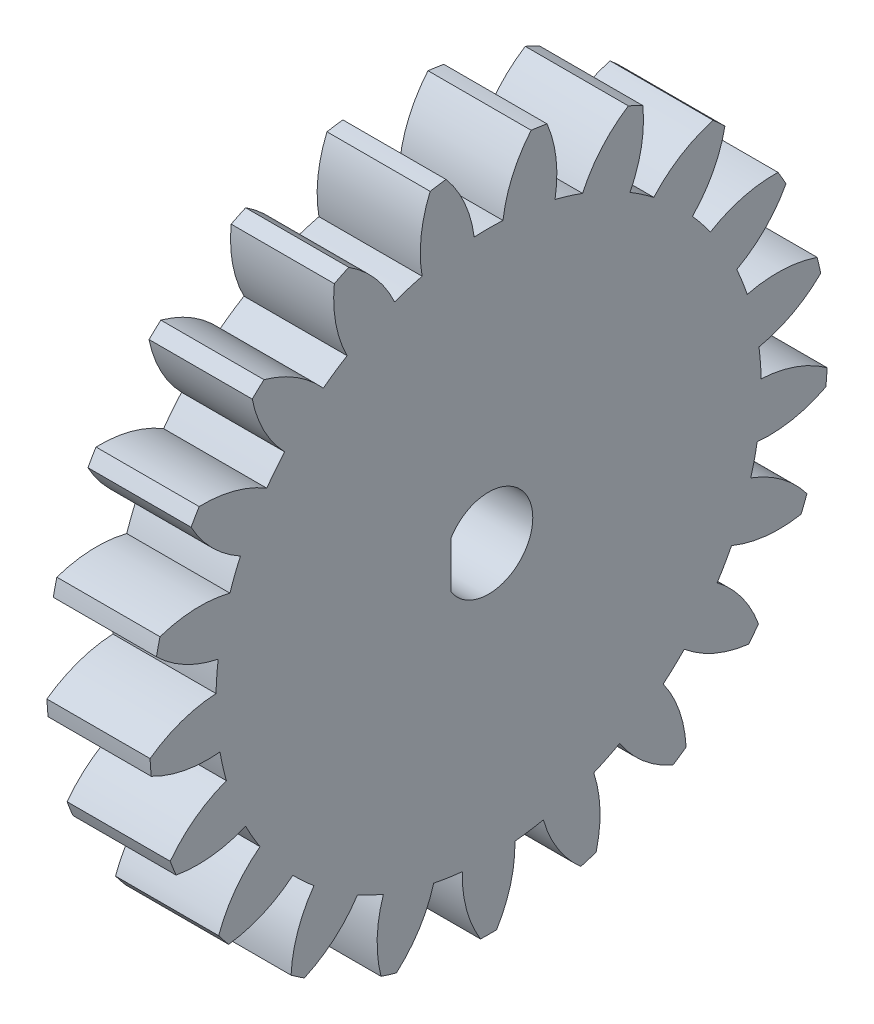
SolidWorks part; units mm, degrees
ref_plane "Plane1" through (0, 0, 0) normal (0, 0, 1) x (1, 0, 0)
ref_plane "Plane2" through (0, 0, 0) normal (0, 1, 0) x (1, 0, 0)
ref_plane "Plane3" through (0, 0, 0) normal (1, 0, 0) x (0, 0, -1)
other "Configuration Table"
sketch "HoldingSke" plane through (0, 0, 0) normal (0, 1, 0) x (1, 0, 0)
  line L0 (0, 0) -> (0.4668, -0.1792)
  line L1 (-15, 0) -> (100, 0) construction
  line L2 (0, 0) -> (-2.1039, 2.3779)
  line L3 (0, 0) -> (-11.863, 4.5341)
  line L4 (0, 0) -> (8.0624, 3.0949)
  line L5 (0, 0) -> (-11.2434, -4.1935)
  line L6 (0, 0) -> (-5.8027, -3.9151)
  line L7 (-2.1039, 2.3779) -> (0.4791, 14.0966)
  line L8 (-76.2, 54.61) -> (-75.2, 54.61)
  line L9 (-71.009, 38.7566) -> (-53.1078, 45.2721)
  line L10 (-76.2, 71.12) -> (104.1128, 71.12)
  line L11 (0, 0) -> (-7, 0)
  line L12 (-76.2, 101.6) -> (-76.133, 101.6)
  line L13 (24.9733, 27.94) -> (52.9518, 28.4284)
  line L14 (24.9733, 27.94) -> (24.9743, 27.94)
  line L15 (24.9733, 27.94) -> (100.4006, 29.5858)
  line L16 (-63.627, -2) -> (-12.827, -2)
  circle A0 centre (0, 0) radius 3
  circle A1 centre (0, 0) radius 5
  circle A2 centre (0, 0) radius 5
  circle A3 centre (0, 0) radius 3
  dimension "MHD" = 10
  dimension "Hub_dia" = 10
  dimension "Bore" = 6
  dimension "MBD" = 6
  dimension "Num_teeth" = 21
  dimension "Pitch" = 0.5
  dimension "Overall_len" = 12
  dimension "Show_teeth" = 21
  dimension "Thickness" = 7
  dimension "OAL" = 12.0001
  dimension "T_dim" = 1
  dimension "Ap" = 20
  dimension "H" = 19.05
  dimension "Pitch_radius" = 180.3128
  dimension "Width" = 7
  dimension "Backlash" = 0.067
  dimension "Addendum_fac" = 1
  dimension "Dedendum_fac" = 1.25
  dimension "Clearance_fac" = 0.25
  dimension "Dedendum_add" = 0.001
  dimension "Module" = 2
sketch "BasProSke" plane through (0, 0, 0) normal (0, 1, 0) x (1, 0, 0)
  line L0 (-10, 0) -> (60, 0) construction
  line L1 (0, 0) -> (0, 23)
  line L2 (0, 0) -> (7, 0)
  line L3 (7, 0) -> (7, 23)
  line L4 (7, 23) -> (0, 23)
  dimension "Thickness" = 7
  dimension "Diameter" = 46
revolve "Base-Revolve" add sketch "BasProSke" angle 360 about L0
sketch "TooCutSke" plane through (0, 0, 0) normal (1, 0, 0) x (0, 0, -1)
  line L1 (0, 0) -> (0, 107) construction
  line L2 (0, 0) -> (-1.6865, 20.9322) construction
  line L3 (0, 0) -> (-6.2448, 41.4315) construction
  line L4 (-1.6865, 20.9322) -> (-3.1224, 20.7157) construction
  arc A0 (0.9768, 18.4732) -> (-0.9768, 18.4732) centre (0, 0) ccw
  arc A1 (2.908, 22.841) -> (-2.908, 22.841) centre (0, 0) ccw
  circle A2 centre (0, 0) radius 21 construction
  circle A3 centre (0, 0) radius 19.7335 construction
  arc A4 (-0.9768, 18.4732) -> (-2.908, 22.841) centre (-9.308, 17.4004) ccw
  arc A5 (2.908, 22.841) -> (0.9768, 18.4732) centre (9.308, 17.4004) ccw
  dimension "Root_dia" = 36.998
  dimension "Overcut_dia" = 46.0508
  dimension "Pitch_dia" = 42
  dimension "Base_dia" = 39.4671
  dimension "Flank_rad" = 8.4
  dimension "Half_ang" = 8.571
  dimension "Half_CT" = 1.4521
extrude "ToothCut" cut sketch "TooCutSke" along normal through all
fillet "Breaks" [suppressed] radius 0.04
fillet "RootFillets" [suppressed] radius 0.501
pattern_circular "TeethCuts" count 21 every 17.143 about axis through (-10, 0, 0) along (1, 0, 0) of "ToothCut", "RootFillets", "Breaks"
sketch "HubNeaOneSke" plane through (0, 0, 0) normal (-1, 0, 0) x (0, 0, 1)
  circle A0 centre (0, 0) radius 5
  dimension "Diameter" = 10
extrude "HubNearOne" add sketch "HubNeaOneSke" along normal blind 5.0001
sketch "HubNeaBotSke" plane through (0, 0, 0) normal (-1, 0, 0) x (0, 0, 1)
  circle A0 centre (0, 0) radius 5
  dimension "Diameter" = 10
extrude "HubNearBoth" [suppressed] add sketch "HubNeaBotSke" along normal blind 2.5
ref_plane "FarPln" through (7, 0, 0) normal (1, 0, 0) x (0, 0, -1)
sketch "HubFarSke" plane through (7, 0, 0) normal (1, 0, 0) x (0, 0, -1)
  circle A0 centre (0, 0) radius 5
  dimension "Diameter" = 10
extrude "HubFar" [suppressed] add sketch "HubFarSke" along normal blind 2.5
sketch "BorSke" plane through (0, 0, 0) normal (1, 0, 0) x (0, 0, -1)
  circle A0 centre (0, 0) radius 3
  dimension "Diameter" = 6
extrude "Bore" cut sketch "BorSke" along normal mid plane 24.0001
sketch "KeySke" plane through (0, 0, 0) normal (1, 0, 0) x (0, 0, -1)
  line L0 (-1, 0) -> (-1, 4)
  line L1 (-1, 4) -> (1, 4)
  line L2 (1, 4) -> (1, 0)
  line L3 (0, 0) -> (0, 34) construction
  line L4 (-1, 0) -> (1, 0)
  dimension "Offset" = 4
  dimension "Width" = 2
extrude "Keyway" [suppressed] cut sketch "KeySke" along normal mid plane 24.0001
pattern_circular "Keyway2" [suppressed] count 2 every 90 about axis through (-10, 0, 0) along (1, 0, 0)
sketch "草图1" plane through (-5.0001, 0, 0) normal (-1, 0, 0) x (0, 0, 1)
  line L0 (2.55, 1.5803) -> (2.55, -1.5803)
  arc A0 (2.55, -1.5803) -> (2.55, 1.5803) centre (0, 0) ccw
  dimension "D2" = 6
  dimension "D1" = 2.55
extrude "凸台-拉伸1" add sketch "草图1" against normal through all
sketch "草图3" plane through (0, 0, 0) normal (0, 0, 1) x (1, 0, 0)
  line L1 (-7.99, 0) -> (4.3508, 0) construction
  circle A0 centre (-2.5001, 0) radius 1.65
  dimension "D1" = 3.3
sketch "草图4" plane through (-5.0001, 0, 0) normal (-1, 0, 0) x (0, 0, 1)
  line L0 (0, -1.65) -> (0, 1.65) construction
  line L1 (-4, 3) -> (-4, -3)
  line L2 (4, 3) -> (4, -3)
  arc A0 (-4, 3) -> (-4, -3) centre (0, 0) ccw
  arc A1 (4, -3) -> (4, 3) centre (0, 0) ccw
  dimension "D2" = 4
  dimension "D3" = 10
  dimension "D1" = 4
extrude "切除-拉伸2" cut sketch "草图4" against normal up to surface (5.0001 mm away) up to face at (0, 0, -5)
extrude "切除-拉伸3" cut sketch "草图3" against normal through all both and the other way through all
equation "' \"Module@HoldingSke\" = 6.35"
equation "' \"Num_teeth@HoldingSke\" = 12"
equation "' \"Ap@HoldingSke\" =  20"
equation "' \"Ap@HoldingSke\" = 20"
equation "' \"Width@HoldingSke\" = 0.5 * 25.4"
equation "' \"Hub_dia@HoldingSke\"= 1 * 25.4"
equation "' \"Hub_dia@HoldingSke\" = 1 * 25.4"
equation "' \"Overall_len@HoldingSke\" = 1.0 * 25.4"
equation "' \"Bore@HoldingSke\" = 0.75 * 25.4"
equation "' \"T_dim@HoldingSke\" = 0.1 * 25.4"
equation "' \"Width@KeySke\" = 0.25 * 25.4"
equation "' \"Show_teeth@HoldingSke\" = 13"
equation "' \"Backlash@HoldingSke\" = 0.009 * 25.4"
equation "' \"Addendum_fac@HoldingSke\" = 1.0"
equation "' \"Dedendum_fac@HoldingSke\" = 1.25"
equation "' \"Dedendum_add@HoldingSke\" = 0.00005 * 25.4"
equation "' \"Clearance_fac@HoldingSke\" = 0.25"
equation "\"Pitch@HoldingSke\" = 1 / \"Module@HoldingSke\""
equation "\"Overcut_dia@TooCutSke\" = (\"Num_teeth@HoldingSke\" + 2 * \"Addendum_fac@HoldingSke\") / \"Pitch@HoldingSke\" + 0.002 * 25.4"
equation "\"Pitch_dia@TooCutSke\" = \"Num_teeth@HoldingSke\" / \"Pitch@HoldingSke\""
equation "\"Base_dia@TooCutSke\" = \"Num_teeth@HoldingSke\" / \"Pitch@HoldingSke\" * cos((\"Ap@HoldingSke\"  * 3.14159265 / 180))"
equation "\"Root_dia@TooCutSke\" = (\"Num_teeth@HoldingSke\" + 2) / \"Pitch@HoldingSke\" - 2 * (\"Addendum_fac@HoldingSke\" + \"Dedendum_fac@HoldingSke\") / \"Pitch@HoldingSke\" - \"Dedendum_add@HoldingSke\" * 2"
equation "\"Half_ang@TooCutSke\" = 180 / \"Num_teeth@HoldingSke\""
equation "\"Half_CT@TooCutSke\" = \"Num_teeth@HoldingSke\" / \"Pitch@HoldingSke\" * sin((3.14159265 / 2 / \"Num_teeth@HoldingSke\")) / 2 - 7 * \"Backlash@HoldingSke\" / 4"
equation "\"Flank_rad@TooCutSke\" = \"Num_teeth@HoldingSke\" / \"Pitch@HoldingSke\" / 5"
equation "\"Radius@RootFillets\" = \"Clearance_fac@HoldingSke\" / \"Pitch@HoldingSke\" + \"Dedendum_add@HoldingSke\""
equation "\"Break_rad@Breaks\" = 0.02 / \"Pitch@HoldingSke\""
equation "\"Thickness@HoldingSke\" = \"Width@HoldingSke\""
equation "\"OAL@HoldingSke\" = \"Thickness@HoldingSke\""
equation "\"MHD@HoldingSke\" = (\"Num_teeth@HoldingSke\" + 2) / \"Pitch@HoldingSke\" - 2 * (\"Addendum_fac@HoldingSke\" + \"Dedendum_fac@HoldingSke\")  / \"Pitch@HoldingSke\" - \"Dedendum_add@HoldingSke\" * 2"
equation "\"MBD@HoldingSke\" = (\"Num_teeth@HoldingSke\" + 2) / \"Pitch@HoldingSke\" - 2 * (\"Addendum_fac@HoldingSke\" + \"Dedendum_fac@HoldingSke\")  / \"Pitch@HoldingSke\" - \"Dedendum_add@HoldingSke\" * 2 - 0.002 * 25.4"
equation "\"MHD@HoldingSke\" = ((sgn( \"MHD@HoldingSke\" - \"Hub_dia@HoldingSke\" )-1)*( \"MHD@HoldingSke\" - \"Hub_dia@HoldingSke\" ))/-2+ \"Hub_dia@HoldingSke\""
equation "\"MBD@HoldingSke\" = ((sgn( \"MBD@HoldingSke\" - \"Bore@HoldingSke\" )-1)*( \"MBD@HoldingSke\" - \"Bore@HoldingSke\" ))/-2+ \"Bore@HoldingSke\""
equation "\"OAL@HoldingSke\" = ((sgn( \"OAL@HoldingSke\" - \"Overall_len@HoldingSke\" )+1)*( \"OAL@HoldingSke\" - \"Overall_len@HoldingSke\" ))/2 + \"Overall_len@HoldingSke\" + 0.000002 * 25.4"
equation "\"Num_teeth@TeethCuts\" = int( \"Show_teeth@HoldingSke\" ) + 1"
equation "\"Num_teeth@TeethCuts\" = ((sgn( \"Num_teeth@TeethCuts\" - \"Num_teeth@HoldingSke\" )-1)*( \"Num_teeth@TeethCuts\" - \"Num_teeth@HoldingSke\" ))/-2+ \"Num_teeth@HoldingSke\""
equation "\"Num_teeth@TeethCuts\" = ((sgn( \"Num_teeth@TeethCuts\" - 2.0)+1)*( \"Num_teeth@TeethCuts\" - 2.0))/2 +2.0"
equation "\"Angle@TeethCuts\" = 360.0 / \"Num_teeth@HoldingSke\""
equation "\"Diameter@BasProSke\" = (\"Num_teeth@HoldingSke\" + 2 * \"Addendum_fac@HoldingSke\") / \"Pitch@HoldingSke\""
equation "\"Thickness@BasProSke\"  = \"Thickness@HoldingSke\""
equation "' \"Fillet_rad@BasProSke\" =  \"Thickness@HoldingSke\" * 0.05"
equation "' \"Fillet_rad@BasProSke\" = \"Thickness@HoldingSke\" * 0.05"
equation "\"MHD@HoldingSke\" = ((sgn( \"MHD@HoldingSke\" - \"Root_dia@TooCutSke\" )-1)*( \"MHD@HoldingSke\" - \"Root_dia@TooCutSke\" ))/-2+ \"Root_dia@TooCutSke\""
equation "\"Diameter@HubNeaOneSke\" = \"MHD@HoldingSke\""
equation "\"Length@HubNearOne\" = \"OAL@HoldingSke\" - \"Thickness@BasProSke\""
equation "\"Diameter@HubNeaBotSke\" = \"MHD@HoldingSke\""
equation "\"Length@HubNearBoth\" = ( \"OAL@HoldingSke\" - \"Thickness@BasProSke\" ) / 2.0"
equation "\"Thickness@FarPln\" = \"Thickness@BasProSke\""
equation "\"Diameter@HubFarSke\" = \"MHD@HoldingSke\""
equation "\"Length@HubFar\" = ( \"OAL@HoldingSke\" - \"Thickness@BasProSke\" ) / 2.0"
equation "\"Diameter@BorSke\" = \"MBD@HoldingSke\""
equation "\"D1@Bore\" = \"OAL@HoldingSke\" * 2.0"
equation "\"D1@Keyway\" = \"OAL@HoldingSke\" * 2.0"
equation "\"Offset@KeySke\" = \"T_dim@HoldingSke\" + \"MBD@HoldingSke\" / 2.0"
